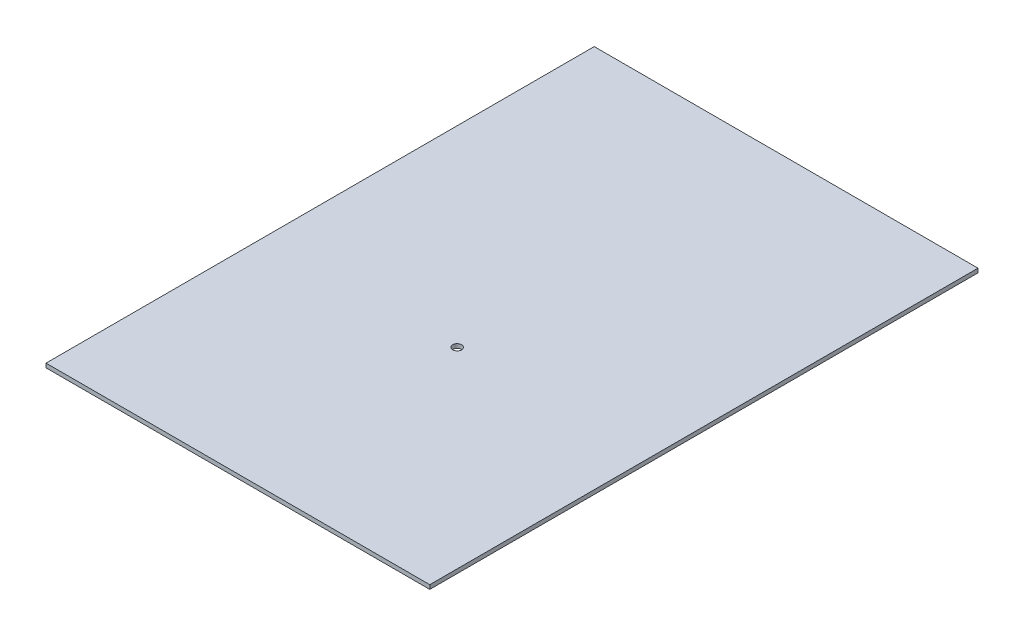
SolidWorks part; units mm, degrees
ref_plane "Front Plane" through (0, 0, 0) normal (0, 0, 1) x (1, 0, 0)
ref_plane "Top Plane" through (0, 0, 0) normal (0, 1, 0) x (1, 0, 0)
ref_plane "Right Plane" through (0, 0, 0) normal (1, 0, 0) x (0, 0, -1)
sketch "Sketch1" plane through (0, 0, 0) normal (0, 1, 0) x (1, 0, 0)
  line L1 (0, 0) -> (280, 0)
  line L2 (0, 0) -> (0, 400)
  line L3 (0, 400) -> (280, 400)
  line L4 (280, 0) -> (280, 400)
  circle A0 centre (140, 160) radius 3.25
  dimension "D1" = 140
  dimension "D4" = 240
  dimension "D5" = 6.5
  dimension "D2" = 400
  dimension "D3" = 280
extrude "Boss-Extrude1" add sketch "Sketch1" along normal blind 3
